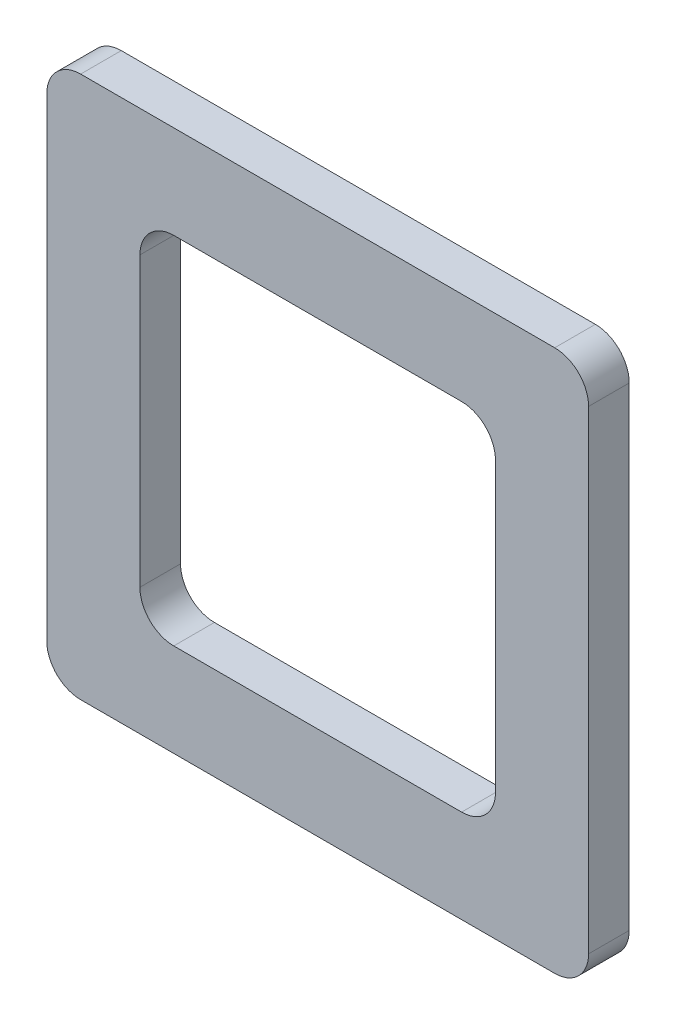
SolidWorks part; units mm, degrees
ref_plane "Front Plane" through (0, 0, 0) normal (0, 0, 1) x (1, 0, 0)
ref_plane "Top Plane" through (0, 0, 0) normal (0, 1, 0) x (1, 0, 0)
ref_plane "Right Plane" through (0, 0, 0) normal (1, 0, 0) x (0, 0, -1)
sketch "Sketch1" plane through (0, 0, 0) normal (0, 0, 1) x (1, 0, 0)
  line L1 (10, 0) -> (150, 0)
  line L2 (0, 10) -> (0, 150)
  line L3 (10, 160) -> (150, 160)
  line L4 (160, 10) -> (160, 150)
  arc A0 (0, 150) -> (10, 160) centre (10, 150) cw
  arc A1 (150, 160) -> (160, 150) centre (150, 150) cw
  arc A2 (10, 0) -> (0, 10) centre (10, 10) cw
  arc A3 (150, 0) -> (160, 10) centre (150, 10) ccw
  point P6 (0, 160)
  point P11 (0, 0)
  point P14 (160, 0)
  dimension "D3" = 10
  dimension "D1" = 160
  dimension "D2" = 160
extrude "Extrude1" add sketch "Sketch1" along normal blind 12
sketch "Sketch2" plane through (0, 0, 12) normal (0, 0, 1) x (1, 0, 0)
  line L31 (27.5, 132.5) -> (27.5, 27.5)
  line L32 (27.5, 27.5) -> (132.5, 27.5)
  line L33 (132.5, 27.5) -> (132.5, 132.5)
  line L34 (132.5, 132.5) -> (27.5, 132.5)
  line L35 (27.5, 122.5) -> (27.5, 37.5)
  line L36 (37.5, 27.5) -> (122.5, 27.5)
  line L37 (132.5, 37.5) -> (132.5, 122.5)
  line L38 (122.5, 132.5) -> (37.5, 132.5)
  arc A17 (27.5, 122.5) -> (37.5, 132.5) centre (37.5, 122.5) cw
  arc A18 (132.5, 122.5) -> (122.5, 132.5) centre (122.5, 122.5) ccw
  arc A19 (122.5, 27.5) -> (132.5, 37.5) centre (122.5, 37.5) ccw
  arc A20 (27.5, 37.5) -> (37.5, 27.5) centre (37.5, 37.5) ccw
  dimension "D2" = 10
  dimension "D1" = 27.5
extrude "Cut-Extrude1" cut sketch "Sketch2" against normal through all
